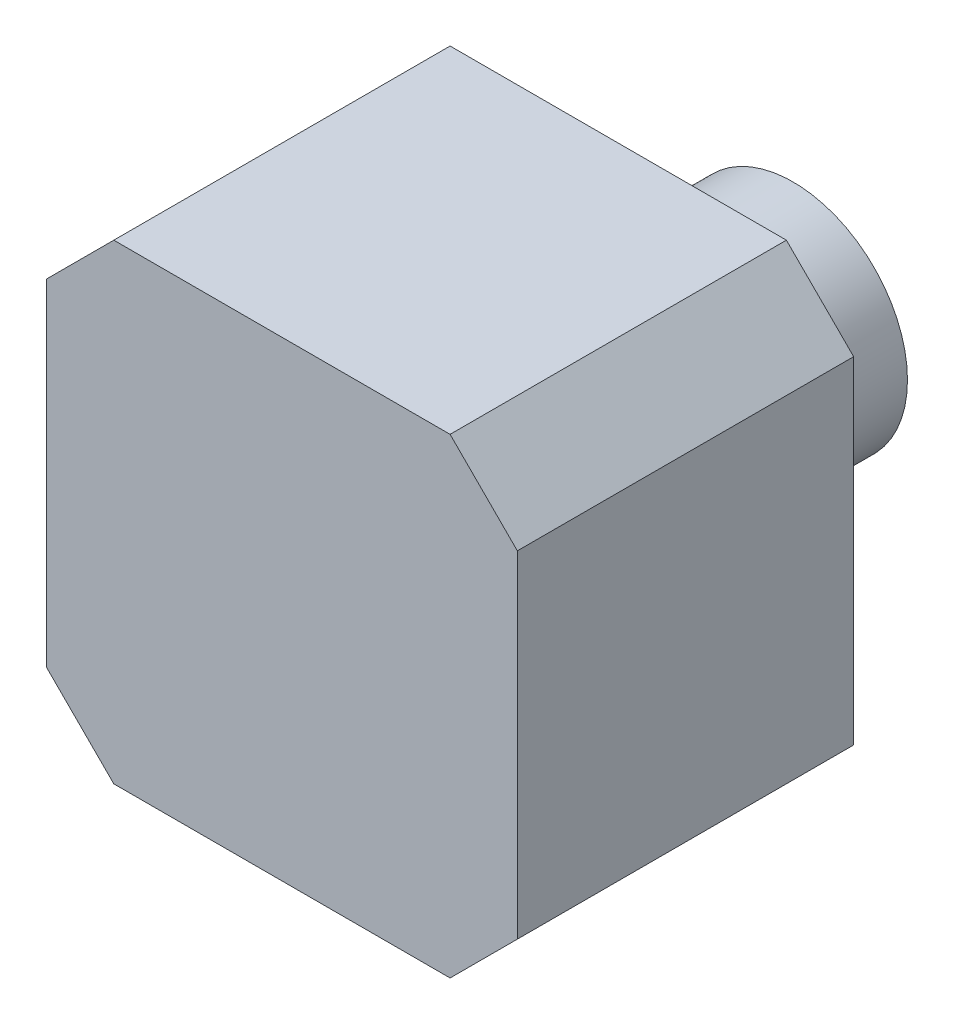
SolidWorks part; units mm, degrees
ref_plane "Front" through (0, 0, 0) normal (0, 0, 1) x (1, 0, 0)
ref_plane "Top" through (0, 0, 0) normal (0, 1, 0) x (1, 0, 0)
ref_plane "Right" through (0, 0, 0) normal (1, 0, 0) x (0, 0, -1)
sketch "Эскиз1" plane through (0, 0, 0) normal (0, 0, 1) x (1, 0, 0)
  line L1 (-17.5, -17.5) -> (17.5, -17.5)
  line L2 (-17.5, -17.5) -> (-17.5, 17.5)
  line L3 (-17.5, 17.5) -> (17.5, 17.5)
  line L4 (17.5, -17.5) -> (17.5, 17.5)
  line L5 (-17.5, -17.5) -> (17.5, 17.5) construction
  line L6 (-17.5, 17.5) -> (17.5, -17.5) construction
  point P0 (0, 0)
extrude "Бобышка-Вытянуть1" add sketch "Эскиз1" along normal blind 25
chamfer "Фаска1" distance 5 angle 45 4 edges at (-17.5, -17.5, 12.5) (17.5, -17.5, 12.5) (17.5, 17.5, 12.5) (-17.5, 17.5, 12.5)
sketch "Эскиз2" plane through (0, 0, 0) normal (0, 0, -1) x (-1, 0, 0)
  circle A0 centre (0, 0) radius 11
  dimension "D1" = 22
extrude "Бобышка-Вытянуть2" add sketch "Эскиз2" along normal blind 2
sketch "Эскиз3" plane through (0, 0, -2) normal (0, 0, -1) x (-1, 0, 0)
  circle A0 centre (0, 0) radius 8.5
extrude "Бобышка-Вытянуть3" add sketch "Эскиз3" along normal blind 11
